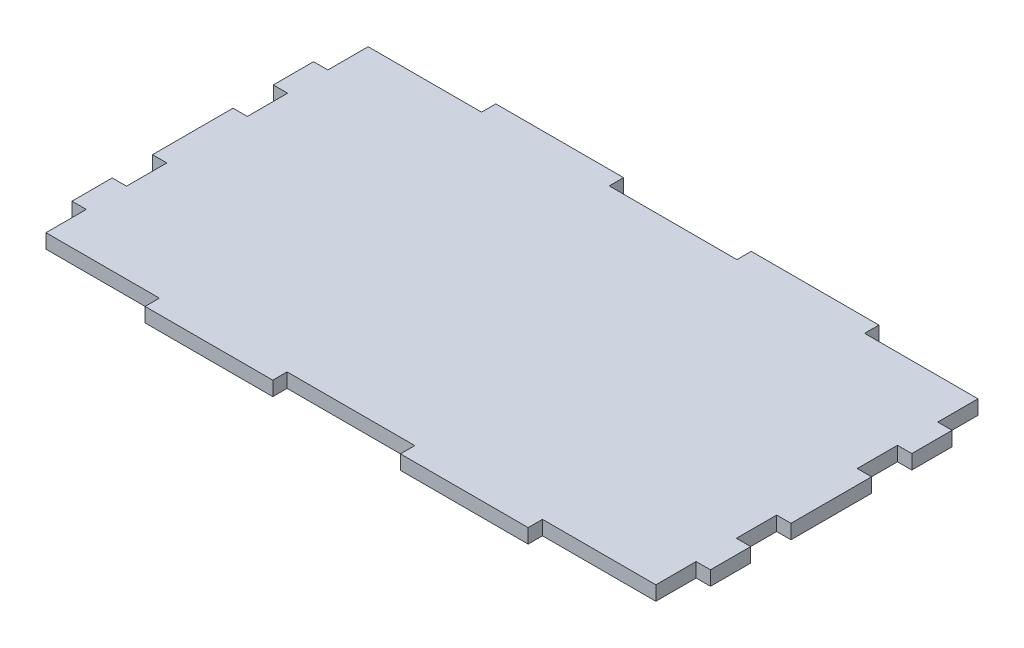
SolidWorks part; units mm, degrees
ref_plane "Front Plane" through (0, 0, 0) normal (0, 0, 1) x (1, 0, 0)
ref_plane "Top Plane" through (0, 0, 0) normal (0, 1, 0) x (1, 0, 0)
ref_plane "Right Plane" through (0, 0, 0) normal (1, 0, 0) x (0, 0, -1)
sketch "Sketch1" plane through (0, 0, 0) normal (0, 1, 0) x (1, 0, 0)
  line L1 (-354.9818, 36.9171) -> (154.7657, 36.9171)
  line L2 (-354.9818, 36.9171) -> (-354.9818, -243.1306)
  line L3 (-354.9818, -243.1306) -> (154.7657, -243.1306)
  line L4 (154.7657, 36.9171) -> (154.7657, -243.1306)
  dimension "D1" = 509.7475
  dimension "D2" = 280.0477
extrude "Boss-Extrude1" add sketch "Sketch1" along normal blind 11.43
sketch "Sketch2" plane through (0, 11.43, 0) normal (0, 1, 0) x (1, 0, 0)
  line L0 (-100.108, 36.9171) -> (-100.108, -243.1306) construction
  line L1 (154.7657, 36.9171) -> (-354.9818, 36.9171) construction
  line L2 (-354.9818, -243.1306) -> (154.7657, -243.1306) construction
  line L3 (-354.9818, -103.1067) -> (154.7657, -103.1067) construction
  line L4 (-354.9818, 36.9171) -> (-354.9818, -243.1306) construction
  line L5 (154.7657, -243.1306) -> (154.7657, 36.9171) construction
  line L6 (-49.1333, 25.4871) -> (-151.0828, 25.4871)
  line L7 (-49.1333, -243.1306) -> (-151.0828, -243.1306)
  line L8 (-100.108, -243.1306) -> (-100.108, -231.7006)
  line L9 (-49.1333, -231.7006) -> (-151.0828, -231.7006)
  line L10 (-151.0828, -243.1306) -> (-151.0828, -231.7006)
  line L11 (-151.0828, -243.1306) -> (-253.0323, -243.1306)
  line L12 (-151.0828, -243.1306) -> (-151.0828, -231.7006)
  line L14 (-253.0323, -243.1306) -> (-253.0323, -231.7006)
  line L15 (-253.0323, -243.1306) -> (-354.9818, -243.1306)
  line L16 (-253.0323, -243.1306) -> (-253.0323, -231.7006)
  line L17 (-253.0323, -231.7006) -> (-354.9818, -231.7006)
  line L18 (-354.9818, -243.1306) -> (-354.9818, -231.7006)
  line L19 (-354.9818, -231.7006) -> (-343.5518, -231.7006)
  line L20 (-354.9818, -231.7006) -> (-354.9818, -199.5521)
  line L21 (-354.9818, -199.5521) -> (-343.5518, -199.5521)
  line L22 (-343.5518, -231.7006) -> (-343.5518, -199.5521)
  line L23 (-354.9818, -135.2552) -> (-343.5518, -135.2552)
  line L24 (-354.9818, -135.2552) -> (-354.9818, -167.4036)
  line L25 (-354.9818, -167.4036) -> (-343.5518, -167.4036)
  line L26 (-343.5518, -135.2552) -> (-343.5518, -167.4036)
  line L27 (-151.0828, 36.9171) -> (-151.0828, 25.4871)
  line L28 (-49.1333, 36.9171) -> (-151.0828, 36.9171)
  line L29 (-100.108, 36.9171) -> (-100.108, 25.4871)
  line L30 (-253.0323, 25.4871) -> (-354.9818, 25.4871)
  line L31 (-354.9818, 36.9171) -> (-354.9818, 25.4871)
  line L32 (-253.0323, 36.9171) -> (-354.9818, 36.9171)
  line L33 (-253.0323, 36.9171) -> (-253.0323, 25.4871)
  line L34 (-354.9818, -6.6613) -> (-343.5518, -6.6613)
  line L35 (-343.5518, 25.4871) -> (-343.5518, -6.6613)
  line L36 (-354.9818, 25.4871) -> (-343.5518, 25.4871)
  line L37 (-354.9818, 25.4871) -> (-354.9818, -6.6613)
  line L38 (-354.9818, -38.8098) -> (-343.5518, -38.8098)
  line L39 (-343.5518, -70.9583) -> (-343.5518, -38.8098)
  line L40 (-354.9818, -70.9583) -> (-343.5518, -70.9583)
  line L41 (-354.9818, -70.9583) -> (-354.9818, -38.8098)
  line L42 (-49.1333, -243.1306) -> (-49.1333, -231.7006)
  line L43 (52.8162, -231.7006) -> (154.7657, -231.7006)
  line L44 (154.7657, -243.1306) -> (154.7657, -231.7006)
  line L45 (52.8162, -243.1306) -> (154.7657, -243.1306)
  line L46 (52.8162, -243.1306) -> (52.8162, -231.7006)
  line L47 (154.7657, -199.5521) -> (143.3357, -199.5521)
  line L48 (143.3357, -231.7006) -> (143.3357, -199.5521)
  line L49 (154.7657, -231.7006) -> (143.3357, -231.7006)
  line L50 (154.7657, -231.7006) -> (154.7657, -199.5521)
  line L51 (154.7657, -167.4036) -> (143.3357, -167.4036)
  line L52 (143.3357, -135.2552) -> (143.3357, -167.4036)
  line L53 (154.7657, -135.2552) -> (143.3357, -135.2552)
  line L54 (154.7657, -135.2552) -> (154.7657, -167.4036)
  line L55 (154.7657, -70.9583) -> (154.7657, -38.8098)
  line L56 (154.7657, -70.9583) -> (143.3357, -70.9583)
  line L57 (143.3357, -70.9583) -> (143.3357, -38.8098)
  line L58 (154.7657, -38.8098) -> (143.3357, -38.8098)
  line L59 (154.7657, 25.4871) -> (143.3357, 25.4871)
  line L60 (143.3357, 25.4871) -> (143.3357, -6.6613)
  line L61 (154.7657, -6.6613) -> (143.3357, -6.6613)
  line L62 (154.7657, 25.4871) -> (154.7657, -6.6613)
  line L63 (52.8162, 25.4871) -> (154.7657, 25.4871)
  line L64 (52.8162, 36.9171) -> (52.8162, 25.4871)
  line L65 (52.8162, 36.9171) -> (154.7657, 36.9171)
  line L66 (154.7657, 36.9171) -> (154.7657, 25.4871)
  line L67 (-49.1333, 36.9171) -> (-49.1333, 25.4871)
  point P26 (-100.108, -103.1067)
  line M1 (-354.9818, 36.9171) -> (-354.9818, -243.1306)
  line M2 (-354.9818, -243.1306) -> (154.7657, -243.1306)
  dimension "D1" = 11.43
  dimension "D2" = 11.43
  dimension "D3" = 101.9495
  dimension "D4" = 50.9748
  dimension "D5" = 101.9495
  dimension "D6" = 11.43
  dimension "D7" = 11.43
  dimension "D8" = 32.1485
  dimension "D9" = 32.1485
  dimension "D10" = 32.1485
  dimension "D11" = 32.1485
extrude "Cut-Extrude1" cut sketch "Sketch2" against normal through all contours L26 L23 L25 M1 | L17 L22 L21 M1 | L14 L17 M1 M2 | L7 L42 L9 L8 | L10 L8 L9 M2 | L44 L45 L46 L43 | L50 L47 L48 L49 | L51 L52 L53 L54 | L55 L58 L57 L56 | L59 L60 L61 L62 | L66 L65 L64 L63 | L28 L27 L6 L67 | L38 L39 L40 L41 | L37 L34 L35 L36 | L31 L32 L33 L30
equation "\"D1@Sketch1\"=\"Base Length@Assembled Container.Assembly\""
equation "\"D2@Sketch1\"=\"Base Width@Assembled Container.Assembly\""
equation "\"D1@Boss-Extrude1\"=\"Acrylic Thickness@Assembled Container.Assembly\""
equation "\"D1@Sketch2\"=\"Acrylic Thickness@Assembled Container.Assembly\""
equation "\"D2@Sketch2\"=\"Acrylic Thickness@Assembled Container.Assembly\""
equation "\"D4@Sketch2\"=\"Lid Long Side Inner Cutout@Assembled Container.Assembly\""
equation "\"D3@Sketch2\"=\"Lid Long Side Outer Cutout@Assembled Container.Assembly\""
equation "\"D6@Sketch2\"=\"Acrylic Thickness@Assembled Container.Assembly\""
equation "\"D7@Sketch2\"=\"Acrylic Thickness@Assembled Container.Assembly\""
equation "\"D8@Sketch2\"=\"Lid Short Side Outer Cutout@Assembled Container.Assembly\""
equation "\"D9@Sketch2\"=\"Lid Short Side Outer Overhang@Assembled Container.Assembly\""
equation "\"D10@Sketch2\"=\"Lid Short Side Middle Cutout@Assembled Container.Assembly\""
